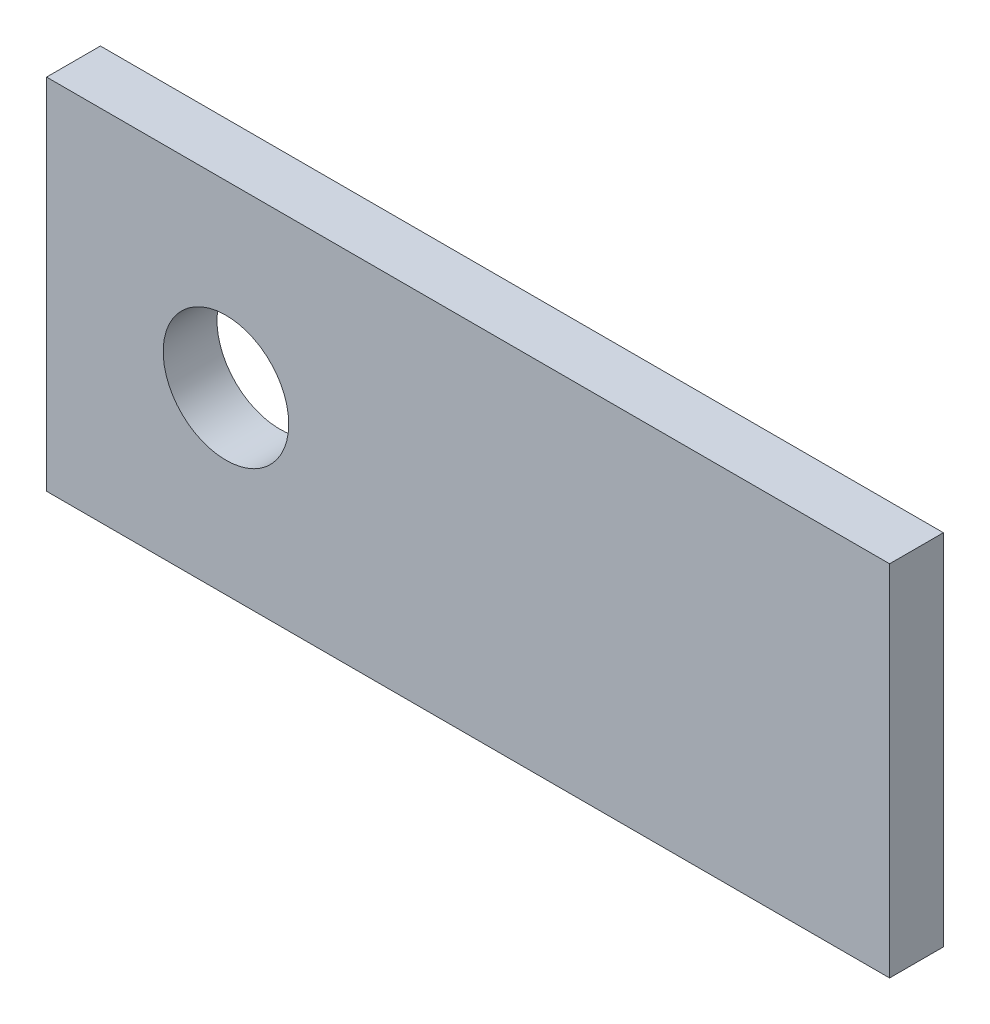
SolidWorks part; units mm, degrees
ref_plane "Plan de face" through (0, 0, 0) normal (0, 0, 1) x (1, 0, 0)
ref_plane "Plan de dessus" through (0, 0, 0) normal (0, 1, 0) x (1, 0, 0)
ref_plane "Plan de droite" through (0, 0, 0) normal (1, 0, 0) x (0, 0, -1)
sketch "Esquisse1" plane through (0, 0, 0) normal (0, 0, 1) x (1, 0, 0)
  line L1 (0, 0) -> (4.7, 0)
  line L2 (0, 0) -> (0, -2)
  line L3 (0, -2) -> (4.7, -2)
  line L4 (4.7, 0) -> (4.7, -2)
  circle A0 centre (1, -1) radius 0.35
  dimension "D4" = 0.7
  dimension "D1" = 4.7
  dimension "D2" = 2
  dimension "D3" = 1
  dimension "D5" = 1
extrude "Boss.-Extru.1" add sketch "Esquisse1" along normal blind 0.3
